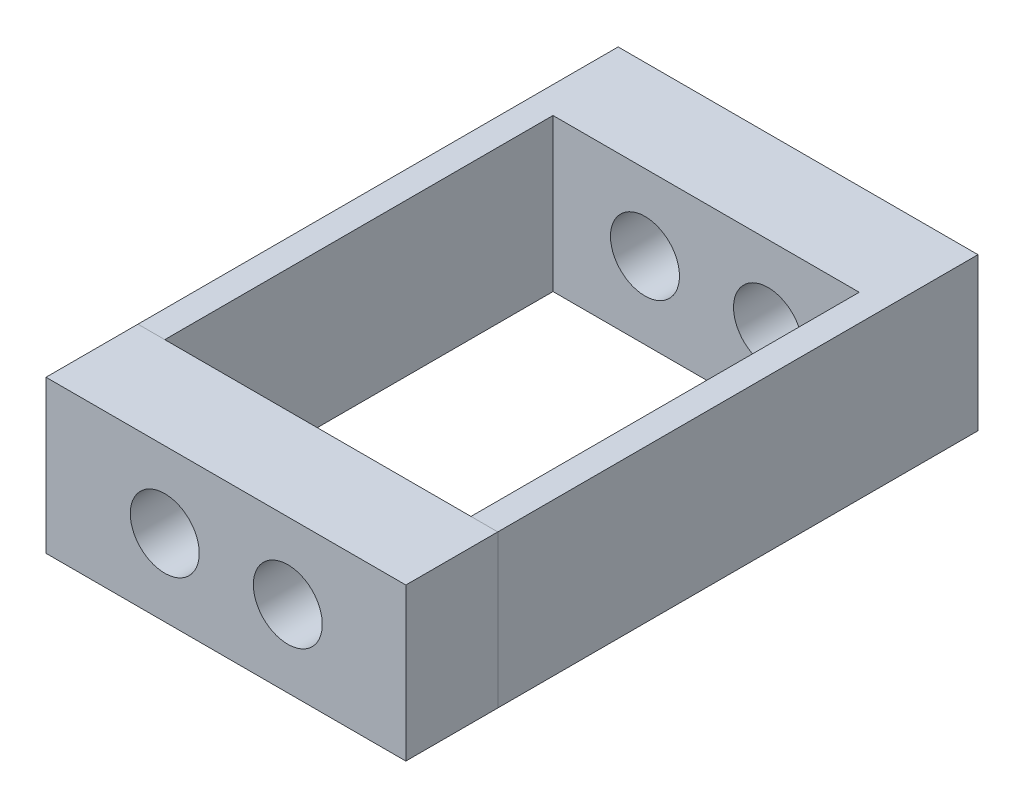
SolidWorks part; units mm, degrees
ref_plane "Front Plane" through (0, 0, 0) normal (0, 0, 1) x (1, 0, 0)
ref_plane "Top Plane" through (0, 0, 0) normal (0, 1, 0) x (1, 0, 0)
ref_plane "Right Plane" through (0, 0, 0) normal (1, 0, 0) x (0, 0, -1)
ref_plane "Plane1" through (0, 31.4462, 0) normal (0, 1, 0) x (1, 0, 0)
ref_plane "Plane2" through (0, -31.75, 0) normal (0, 1, 0) x (1, 0, 0)
sketch "Sketch1" plane through (0, 0, 0) normal (0, 1, 0) x (1, 0, 0)
  line L0 (60.5155, -105.2322) -> (41.4655, -105.2322) construction
  line L1 (-38.1, -98.8822) -> (88.7867, -98.8822)
  line L2 (-38.1, -98.8822) -> (-38.1, -259.7658)
  line L3 (-38.1, -259.7658) -> (88.7867, -259.7658)
  line L4 (88.7867, -98.8822) -> (88.7867, -259.7658)
  line L5 (-9.525, -256.5908) -> (9.525, -256.5908) construction
  line L6 (-31.75, -155.8798) -> (-31.75, -154.0002) construction
  line L7 (82.4367, -164.0078) -> (82.4367, -162.1282) construction
  line L8 (-49.2125, -297.8658) -> (99.8992, -297.8658)
  line L9 (126.8867, -60.7822) -> (126.8867, -297.8658) construction
  line L10 (-49.2125, -60.7822) -> (99.8992, -60.7822)
  line L11 (-76.2, -60.7822) -> (-76.2, -297.8658) construction
  line L12 (99.8992, -60.7822) -> (99.8992, -297.8658)
  line L13 (-49.2125, -60.7822) -> (-49.2125, -297.8658)
  line L14 (-76.2, -60.7822) -> (-49.2125, -60.7822) construction
  line L15 (-76.2, -60.7822) -> (126.8867, -60.7822) construction
  line L16 (-76.2, -297.8658) -> (-49.2125, -297.8658) construction
  line L17 (-76.2, -297.8658) -> (126.8867, -297.8658) construction
  line L18 (99.8992, -297.8658) -> (126.8867, -297.8658) construction
  line L19 (99.8992, -60.7822) -> (126.8867, -60.7822) construction
  dimension "D1" = 6.35
  dimension "D2" = 3.175
  dimension "D3" = 6.35
  dimension "D4" = 6.35
  dimension "D6" = 11.1125
  dimension "D7" = 11.1125
  dimension "D5" = 38.1
extrude "Boss-Extrude1" add sketch "Sketch1" along normal up to surface (63.1962 mm away) from surface at -31.75 contours L10 L13 L8 L12 L1 L4 L3 L2 up to plane "Plane1" starting at plane "Plane2"
sketch "Sketch2" plane through (0, 0, 297.8658) normal (0, 0, 1) x (1, 0, 0)
  circle A0 centre (0, 0) radius 14.2875
  circle A1 centre (50.9905, 0) radius 14.2875
  circle A2 centre (50.9905, 0) radius 9.525 construction
  circle A3 centre (0, 0) radius 9.525 construction
  dimension "D1" = 28.575
extrude "Cut-Extrude1" cut sketch "Sketch2" against normal through all both and the other way through all
ref_plane "Plane3" through (0, 0, 259.7658) normal (0, 0, -1) x (-1, 0, 0)
ref_plane "Plane4" through (0, 0, 98.8822) normal (0, 0, 1) x (1, 0, 0)
sketch "Sketch3" plane through (0, 0, 259.7658) normal (0, 0, -1) x (-1, 0, 0)
  line L1 (-69.7933, 31.4462) -> (19.1067, 31.4462)
  line L2 (-69.7933, 31.4462) -> (-69.7933, -31.75)
  line L3 (-69.7933, -31.75) -> (19.1067, -31.75)
  line L4 (19.1067, 31.4462) -> (19.1067, -31.75)
  line L6 (-69.7933, -25.5519) -> (19.1067, -25.5519)
  line L7 (-69.7933, 25.2481) -> (19.1067, 25.2481)
  line L8 (-25.3433, 25.2481) -> (-25.3433, -25.5519) construction
  line L9 (-69.7933, -0.1519) -> (19.1067, -0.1519) construction
  line L10 (49.2125, 31.4462) -> (-99.8992, 31.4462) construction
  line L11 (49.2125, -31.75) -> (-99.8992, -31.75) construction
  line L13 (38.1, -0.1519) -> (-88.7867, -0.1519) construction
  line L14 (38.1, 31.4462) -> (38.1, -31.75) construction
  line L15 (-88.7867, 31.4462) -> (-88.7867, -31.75) construction
  point P4 (-25.3433, -0.1519)
  point P16 (-25.3433, -0.1519)
  dimension "D1" = 88.9
  dimension "D2" = 50.8
split "Split1" trim tools "Plane3" bodies to split 102 resulting bodies 110 111
other "Save Bodies1"
